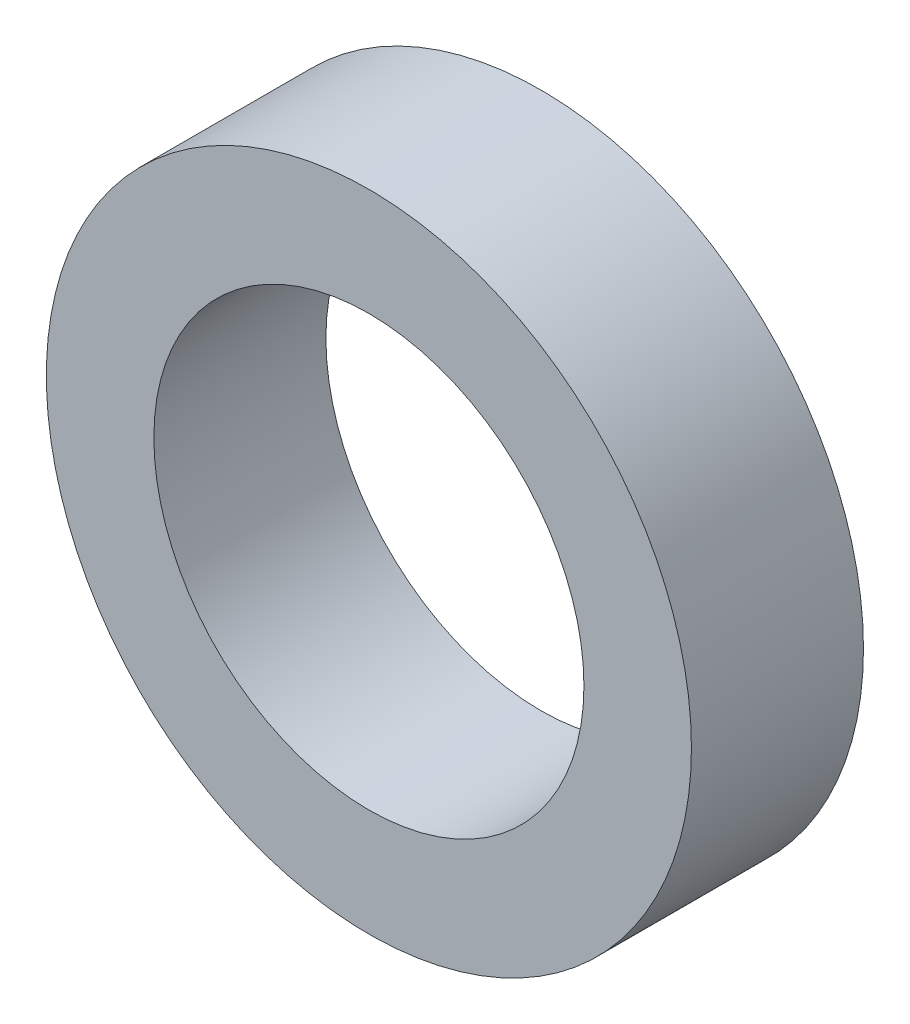
SolidWorks part; units mm, degrees
ref_plane "Front Plane" through (0, 0, 0) normal (1, 0, 0) x (0, 1, 0)
ref_plane "Top Plane" through (0, 0, 0) normal (0, 0, 1) x (0, 1, 0)
ref_plane "Right Plane" through (0, 0, 0) normal (0, 1, 0) x (-1, 0, 0)
sketch "Sketch1" plane through (0, 0, 0) normal (0, 0, 1) x (0, 1, 0)
  circle A0 centre (0, 0) radius 7.5
  circle A1 centre (0, 0) radius 5
  dimension "D1" = 10
  dimension "D2" = 15
extrude "Boss-Extrude1" add sketch "Sketch1" along normal blind 4
